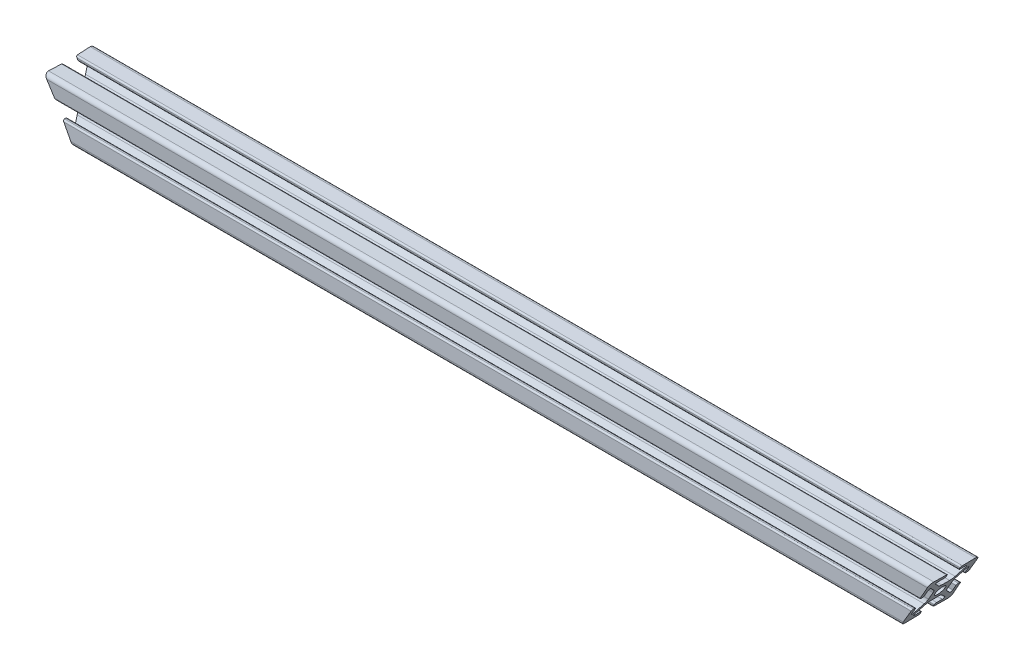
SolidWorks part; units mm, degrees
material "6061-T6 (SS)"
ref_plane "Front Plane" through (0, 0, 0) normal (0, 0, 1) x (1, 0, 0)
ref_plane "Top Plane" through (0, 0, 0) normal (0, 1, 0) x (1, 0, 0)
ref_plane "Right Plane" through (0, 0, 0) normal (1, 0, 0) x (0, 0, -1)
sketch "Sketch1" plane through (0, 0, 0) normal (1, 0, 0) x (0, 0, -1)
  line L0 (0, -12.7) -> (0, 12.7) construction
  line L1 (-7.874, 12.7) -> (7.874, 12.7) construction
  line L2 (-12.7, 0) -> (12.7, 0) construction
  line L3 (-7.874, 12.7) -> (-7.874, 4.826) construction
  line L4 (-3.302, 12.7) -> (3.302, 12.7) construction
  line L5 (-12.7, -12.7) -> (12.7, -12.7) construction
  line L6 (-12.7, 12.7) -> (12.7, 12.7) construction
  circle A0 centre (0, 0) radius 2.54 construction
  point P7 (0, 12.7)
  point P10 (0, 0)
  point P13 (0, 0)
  point P16 (0, 12.7)
  point P17 (-3.302, 12.7)
  point P18 (3.302, 12.7)
  point P21 (0, -12.7)
  point P24 (0, 12.7)
  dimension "Center Hole Diameter" = 5.08
  dimension "Rail Width" = 25.4
  dimension "Rail Height" = 25.4
  dimension "T-Slot Depth" = 7.874
  dimension "D1" = 15.748
  dimension "T-Slot Width" = 6.604
  dimension "D2" = 12.7
sketch "Sketch2" plane through (0, 0, 0) normal (0, 0, 1) x (1, 0, 0)
  line L0 (-224.9527, 0) -> (224.9527, 0) construction
  line L1 (0, 0) -> (0, 26.104) construction
  line L2 (224.9527, -12.7) -> (224.9527, 12.7) construction
  line L3 (-224.9527, -12.7) -> (-224.9527, 12.7) construction
  point P3 (-186.8527, 0)
  point P8 (0, 0)
  point P9 (186.8527, 0)
  point P12 (224.9527, 0)
  point P15 (-224.9527, 0)
  dimension "Length" = 449.9054
  dimension "D1" = 38.1
  dimension "D2" = 25.4
sketch "Sketch3" plane through (0, 0, 0) normal (1, 0, 0) x (0, 0, -1)
  line L0 (0, 4.826) -> (1.9842, 4.826)
  line L1 (0, -12.7) -> (0, 12.7) construction
  line L2 (4.2293, 5.7559) -> (7.5866, 9.1132)
  line L6 (7.0212, 10.4136) -> (4.0906, 10.3112)
  line L7 (3.302, 11.0728) -> (3.302, 11.7082)
  line L8 (-7.874, 12.7) -> (7.874, 12.7) construction
  line L10 (0, 0) -> (12.7, 12.7) construction
  line L13 (0, 4.826) -> (0, 2.54)
  line L14 (4.826, 0) -> (2.54, 0)
  line L31 (4.826, 0) -> (4.826, 1.9842)
  line L32 (4.0374, 12.4697) -> (10.5971, 12.6988)
  line L33 (-12.7, 0) -> (12.7, 0) construction
  line L34 (-12.7, 12.7) -> (12.7, 12.7) construction
  line L35 (5.7559, 4.2293) -> (9.1132, 7.5866)
  line L36 (0, 12.7) -> (12.7, 12.7) construction
  line L37 (12.7, 12.7) -> (12.7, 8.0234) construction
  line L38 (11.0728, 3.302) -> (11.7082, 3.302)
  line L39 (10.4136, 7.0212) -> (10.3112, 4.0906)
  line L40 (12.6988, 10.5971) -> (12.4697, 4.0374)
  arc A0 (2.54, 0) -> (0, 2.54) centre (0, 0) ccw
  arc A1 (1.9842, 4.826) -> (4.2293, 5.7559) centre (1.9842, 8.001) ccw
  circle A2 centre (0, 0) radius 2.54 construction
  arc A7 (3.302, 11.7082) -> (4.0374, 12.4697) centre (4.064, 11.7082) cw
  arc A8 (4.0906, 10.3112) -> (3.302, 11.0728) centre (4.064, 11.0728) cw
  arc A14 (4.826, 1.9842) -> (5.7559, 4.2293) centre (8.001, 1.9842) cw
  arc A16 (10.5971, 12.6988) -> (12.6988, 10.5971) centre (10.668, 10.668) cw
  arc A17 (7.0212, 10.4136) -> (7.5866, 9.1132) centre (7.0478, 9.652) cw
  arc A18 (10.4136, 7.0212) -> (9.1132, 7.5866) centre (9.652, 7.0478) ccw
  arc A19 (10.3112, 4.0906) -> (11.0728, 3.302) centre (11.0728, 4.064) ccw
  arc A20 (11.7082, 3.302) -> (12.4697, 4.0374) centre (11.7082, 4.064) ccw
  point P37 (3.2994, 4.826)
  point P49 (12.7, 3.302)
  point P52 (3.302, 12.7)
  point P55 (3.302, 10.2837)
  dimension "D4" = 3.175
  dimension "D9" = 2.159
  dimension "D12" = 0.762
  dimension "D3" = 2.032
  dimension "D8" = 0.762
  dimension "D2" = 45
  dimension "D5" = 2
  dimension "D6" = 45
  dimension "D7" = 2.159
extrude "Boss-Extrude1" add sketch "Sketch3" against normal up to vertex (224.9527 mm away) and the other way up to vertex (224.9527 mm away) up to point (-224.9527, 0, 0) other way up to point (224.9527, 0, 0)
mirror "Mirror1" about plane through (0, 0, 0) normal (0, 1, 0) of bodies 104
mirror "Mirror2" about plane through (0, 0, 0) normal (0, 0, 1) of bodies 105
sketch "Sketch4" plane through (0, 0, 0) normal (0, 0, 1) x (1, 0, 0)
  line L1 (-227.4927, -38.1) -> (227.4927, -38.1)
  line L3 (224.9527, 12.7) -> (210.288, -12.7)
  line L4 (210.288, -12.7) -> (-210.288, -12.7)
  line L5 (-210.288, -12.7) -> (-224.9527, 12.7)
  line L6 (-224.9527, 12.7) -> (-227.4927, 12.7)
  line L7 (-227.4927, 12.7) -> (-227.4927, -38.1)
  line L8 (224.9527, 12.7) -> (227.4927, 12.7)
  line L9 (227.4927, 12.7) -> (227.4927, -38.1)
  dimension "D2" = 25.4
  dimension "D4" = 25.4
  dimension "D1" = 2.54
  dimension "D3" = 2.54
  dimension "D5" = 30
  dimension "D6" = 30
extrude "Cut-Extrude1" cut sketch "Sketch4" along normal blind 12.7 and the other way blind 12.7 contours L1 L9 L8 L3 L4 L5 L6 L7
ref_plane "Plane3" through (0, 0, -12.6988) normal (0, 0, -1) x (-1, 0, 0)
ref_plane "Plane4" through (0, -12.6988, 0) normal (0, 1, 0) x (1, 0, 0)
ref_plane "Plane5" through (0, 0, 12.6988) normal (0, 0, 1) x (1, 0, 0)
ref_plane "Plane6" through (0, 12.6988, 0) normal (0, -1, 0) x (-1, 0, 0)
equation "\"D1@Sketch2\"=\"Rail Height@Sketch1\"*1.5"
equation "\"D2@Sketch2\"=\"Rail Height@Sketch1\""
equation "\"MaxLength\"= ( \"ROVLength@Assem2.SLDASM\" / COS ( \"Theta@Assem2.SLDASM\" ) ) - ( \"ROVWidth@Assem2.SLDASM\" - \"FaceWidth@Assem2.SLDASM\" ) / ( 2 * TAN ( \"Phi@Assem2.SLDASM\" ) * COS ( \"Theta@Assem2.SLDASM\" ) )"
equation "\"Length@Sketch2\"= \"MaxLength\""
equation "\"LeftCutAngle\"= 45 - ( \"Theta@Assem2.SLDASM\" ) / 2"
equation "\"RightCutAngle\"= ( \"Phi@Assem2.SLDASM\" + \"Theta@Assem2.SLDASM\" ) / 2"
equation "\"BarThickness\"= 1in"
equation "\"InnerLength\"= \"MaxLength\" - TAN ( \"LeftCutAngle\" ) - TAN ( \"RightCutAngle\" )"
equation "\"RightBevelLength\"= tan ( \"RightCutAngle\" )"
equation "\"D2@Sketch4\"=\"BarThickness\""
equation "\"D4@Sketch4\"=\"BarThickness\""
equation "\"D1@Cut-Extrude1\"=\"BarThickness\"/2"
equation "\"D2@Cut-Extrude1\"=\"BarThickness\"/2"
equation "\"D5@Sketch4\"=\"LeftCutAngle\""
equation "\"D6@Sketch4\"=\"RightCutAngle\""
